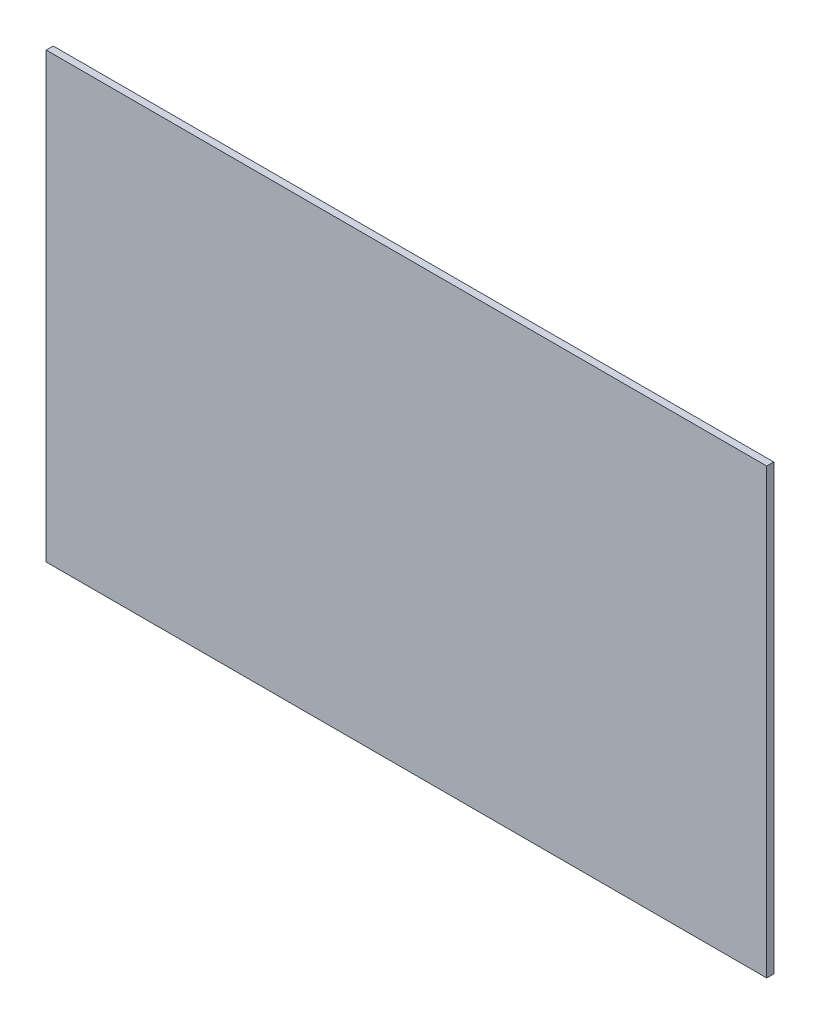
SolidWorks part; units mm, degrees
ref_plane "Alzado" through (0, 0, 0) normal (0, 0, 1) x (1, 0, 0)
ref_plane "Planta" through (0, 0, 0) normal (0, 1, 0) x (1, 0, 0)
ref_plane "Vista lateral" through (0, 0, 0) normal (1, 0, 0) x (0, 0, -1)
sketch "Croquis1" plane through (0, 0, 0) normal (0, 0, 1) x (1, 0, 0)
  line L1 (0, 0) -> (650, 0)
  line L2 (0, 0) -> (0, 400)
  line L3 (0, 400) -> (650, 400)
  line L4 (650, 0) -> (650, 400)
  dimension "D1" = 650
  dimension "D2" = 400
extrude "Saliente-Extruir1" add sketch "Croquis1" along normal blind 6.35
